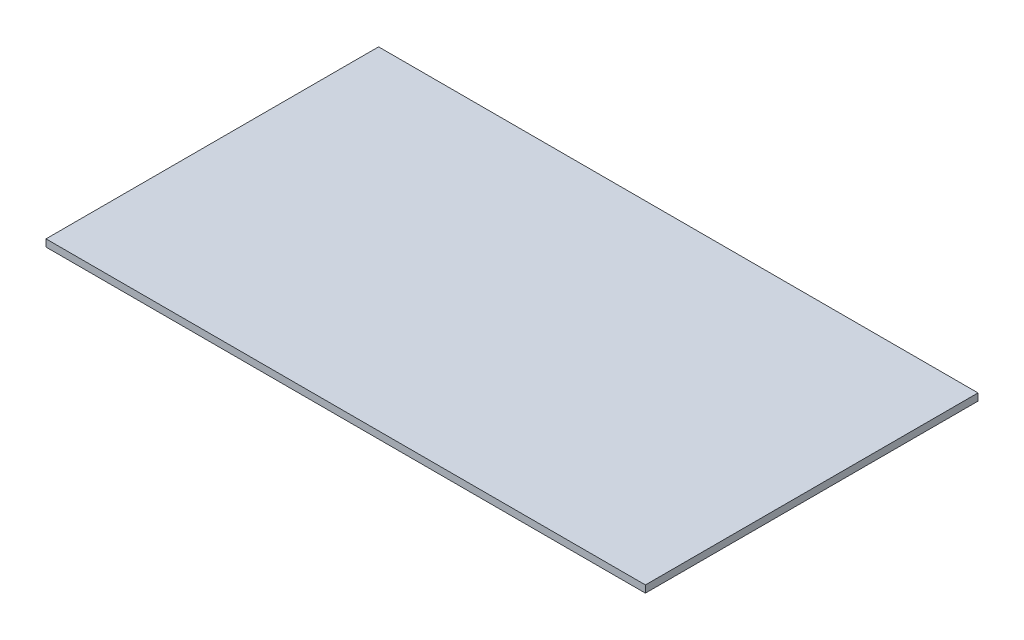
SolidWorks part; units mm, degrees
ref_plane "Front Plane" through (0, 0, 0) normal (0, 0, 1) x (1, 0, 0)
ref_plane "Top Plane" through (0, 0, 0) normal (0, 1, 0) x (1, 0, 0)
ref_plane "Right Plane" through (0, 0, 0) normal (1, 0, 0) x (0, 0, -1)
sketch "Sketch2" plane through (0, 0, 0) normal (0, 1, 0) x (1, 0, 0)
  line L0 (-6.29, 3.49) -> (6.29, 3.49)
  line L1 (-6.29, 3.49) -> (-6.29, -3.49)
  line L2 (-6.29, -3.49) -> (6.29, -3.49)
  line L3 (6.29, 3.49) -> (6.29, -3.49)
  line L4 (-6.29, 3.49) -> (6.29, -3.49) construction
  line L5 (-6.29, -3.49) -> (6.29, 3.49) construction
  point P0 (0, 0)
extrude "Boss-Extrude2" add sketch "Sketch2" along normal mid plane 0.15
